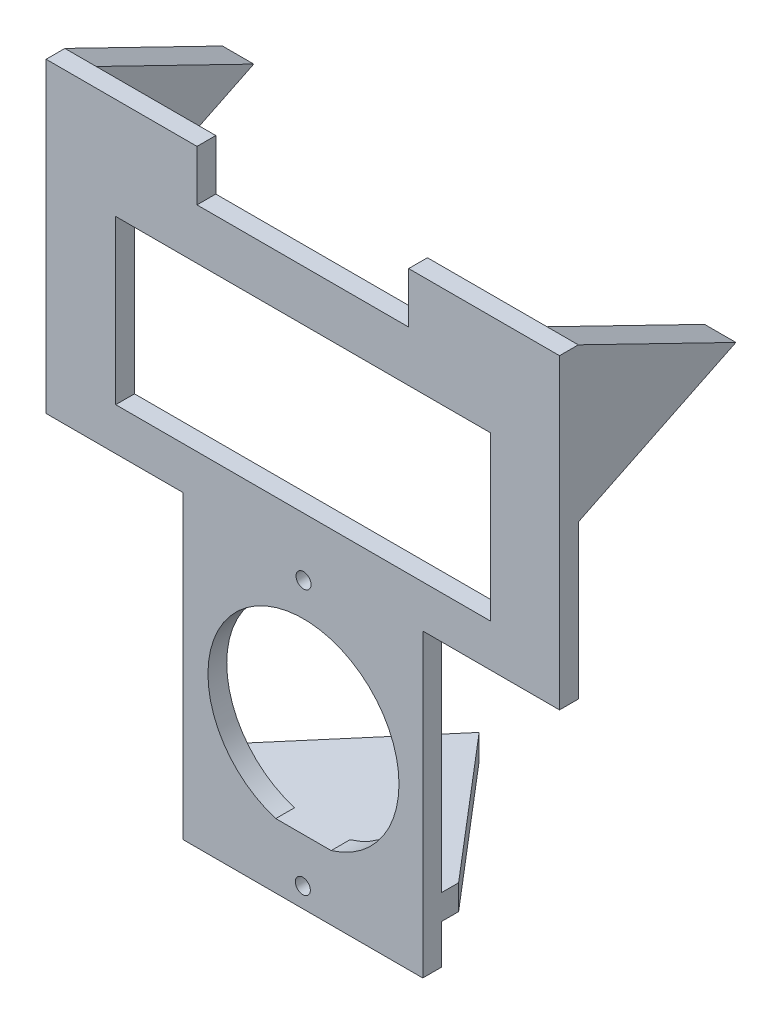
SolidWorks part; units mm, degrees
ref_plane "Plan de face" through (0, 0, 0) normal (0, 0, 1) x (1, 0, 0)
ref_plane "Plan de dessus" through (0, 0, 0) normal (0, 1, 0) x (1, 0, 0)
ref_plane "Plan de droite" through (0, 0, 0) normal (1, 0, 0) x (0, 0, -1)
sketch "Esquisse1" plane through (0, 0, 0) normal (0, 0, 1) x (1, 0, 0)
  line L1 (0, 0) -> (82, 0)
  line L2 (0, 0) -> (0, 49)
  line L3 (0, 49) -> (82, 49)
  line L4 (82, 0) -> (82, 49)
  dimension "D1" = 49
  dimension "D2" = 82
extrude "Boss.-Extru.1" add sketch "Esquisse1" along normal blind 3
sketch "Esquisse2" plane through (0, 0, 0) normal (0, -1, 0) x (1, 0, 0)
  line L0 (41, 0) -> (41, 3) construction
  line L1 (0, 0) -> (82, 0) construction
  line L2 (0, 3) -> (82, 3) construction
  line L4 (21.8453, 3) -> (60.1547, 3)
  line L5 (21.8453, 3) -> (21.8453, 0)
  line L6 (21.8453, 0) -> (60.1547, 0)
  line L7 (60.1547, 3) -> (60.1547, 0)
  line L8 (21.8453, 3) -> (60.1547, 0) construction
  line L9 (21.8453, 0) -> (60.1547, 3) construction
  point P4 (41, 1.5)
extrude "Boss.-Extru.2" add sketch "Esquisse2" along normal blind 48
sketch "Esquisse3" plane through (0, 0, 0) normal (0, 0, -1) x (-1, 0, 0)
  circle A0 centre (-41.1032, -23.0882) radius 15.256
  circle A1 centre (-41.1032, -22.9882) radius 0.1 construction
extrude "Enlèv. mat.-Extru.1" cut sketch "Esquisse3" against normal through all
sketch "Esquisse4" plane through (0, 0, 0) normal (0, 0, -1) x (-1, 0, 0)
  line L0 (-41, 49) -> (-41, -48) construction
  line L1 (-82, 49) -> (0, 49) construction
  line L2 (-21.8453, -48) -> (-60.1547, -48) construction
  line L4 (-57.9007, 40.9074) -> (-24.0993, 40.9074)
  line L5 (-57.9007, 40.9074) -> (-57.9007, 49)
  line L6 (-57.9007, 49) -> (-24.0993, 49)
  line L7 (-24.0993, 40.9074) -> (-24.0993, 49)
  line L8 (-57.9007, 40.9074) -> (-24.0993, 49) construction
  line L9 (-57.9007, 49) -> (-24.0993, 40.9074) construction
  point P6 (-41, 44.9537)
extrude "Enlèv. mat.-Extru.2" cut sketch "Esquisse4" against normal through all
sketch "Esquisse5" plane through (82, 0, 0) normal (1, 0, 0) x (0, 0, -1)
  line L0 (0, 49) -> (0, 24.5)
  line L1 (0, 0) -> (0, 49) construction
  line L2 (0, 24.5) -> (25.166, 36.75)
  line L3 (25.166, 36.75) -> (0, 49)
extrude "Boss.-Extru.3" add sketch "Esquisse5" against normal blind 5
sketch "Esquisse6" plane through (0, 0, 0) normal (-1, 0, 0) x (0, 0, 1)
  line L0 (0, 49) -> (0, 24.5)
  line L1 (0, 49) -> (0, 0) construction
  line L2 (0, 24.5) -> (-25.166, 36.75)
  line L3 (-25.166, 36.75) -> (0, 49)
extrude "Boss.-Extru.4" add sketch "Esquisse6" against normal blind 5
sketch "Esquisse8" plane through (0, 0, 0) normal (0, 0, -1) x (-1, 0, 0)
  line L0 (-41, 40.9074) -> (-41.1298, -7.8322) construction
  line L1 (-57.9007, 40.9074) -> (-24.0993, 40.9074) construction
  circle A0 centre (-41.1032, -23.0882) radius 15.256 construction
  circle A1 centre (-41.1156, -2.5099) radius 1.2
extrude "Enlèv. mat.-Extru.3" cut sketch "Esquisse8" against normal through all
sketch "Esquisse9" plane through (21.8453, 0, 0) normal (-1, 0, 0) x (0, 0, 1)
  line L0 (3, -48) -> (3, 0) construction
  line L1 (3, -37.6879) -> (-2.7242, -37.6879)
  line L2 (3, -37.6879) -> (3, -41.6879)
  line L3 (3, -41.6879) -> (-2.7242, -41.6879)
  line L4 (-2.7242, -37.6879) -> (-2.7242, -41.6879)
  dimension "D1" = 4
extrude "Boss.-Extru.6" add sketch "Esquisse9" against normal up to vertex
sketch "Esquisse10" plane through (0, -41.6879, 0) normal (0, -1, 0) x (1, 0, 0)
  line L0 (21.8453, -2.7242) -> (60.1547, -2.7242)
  line L1 (41, -2.7242) -> (41, -25.1597) construction
  line L2 (60.1547, -2.7242) -> (41, -25.1597)
  line L3 (41, -25.1597) -> (21.8453, -2.7242)
extrude "Boss.-Extru.7" add sketch "Esquisse10" against normal blind 4
sketch "Esquisse11" plane through (0, 0, 0) normal (0, 0, -1) x (-1, 0, 0)
  line L0 (-41, -48) -> (-41, -41.6879) construction
  line L1 (-21.8453, -48) -> (-60.1547, -48) construction
  line L2 (-60.1547, -41.6879) -> (-21.8453, -41.6879) construction
  circle A0 centre (-41, -44.8439) radius 1.2
extrude "Enlèv. mat.-Extru.4" cut sketch "Esquisse11" against normal through all
sketch "Esquisse12" plane through (0, 0, 3) normal (0, 0, 1) x (1, 0, 0)
  line L0 (41, 40.9074) -> (41.1156, -1.3099) construction
  line L1 (57.9007, 40.9074) -> (24.0993, 40.9074) construction
  line L3 (11.1154, 32.8168) -> (71.0002, 32.8168)
  line L4 (11.1154, 32.8168) -> (11.1154, 6.7807)
  line L5 (11.1154, 6.7807) -> (71.0002, 6.7807)
  line L6 (71.0002, 32.8168) -> (71.0002, 6.7807)
  line L7 (11.1154, 32.8168) -> (71.0002, 6.7807) construction
  line L8 (11.1154, 6.7807) -> (71.0002, 32.8168) construction
  circle A0 centre (41.1156, -2.5099) radius 1.2 construction
  point P6 (41.0578, 19.7988)
extrude "Enlèv. mat.-Extru.5" cut sketch "Esquisse12" against normal through all
